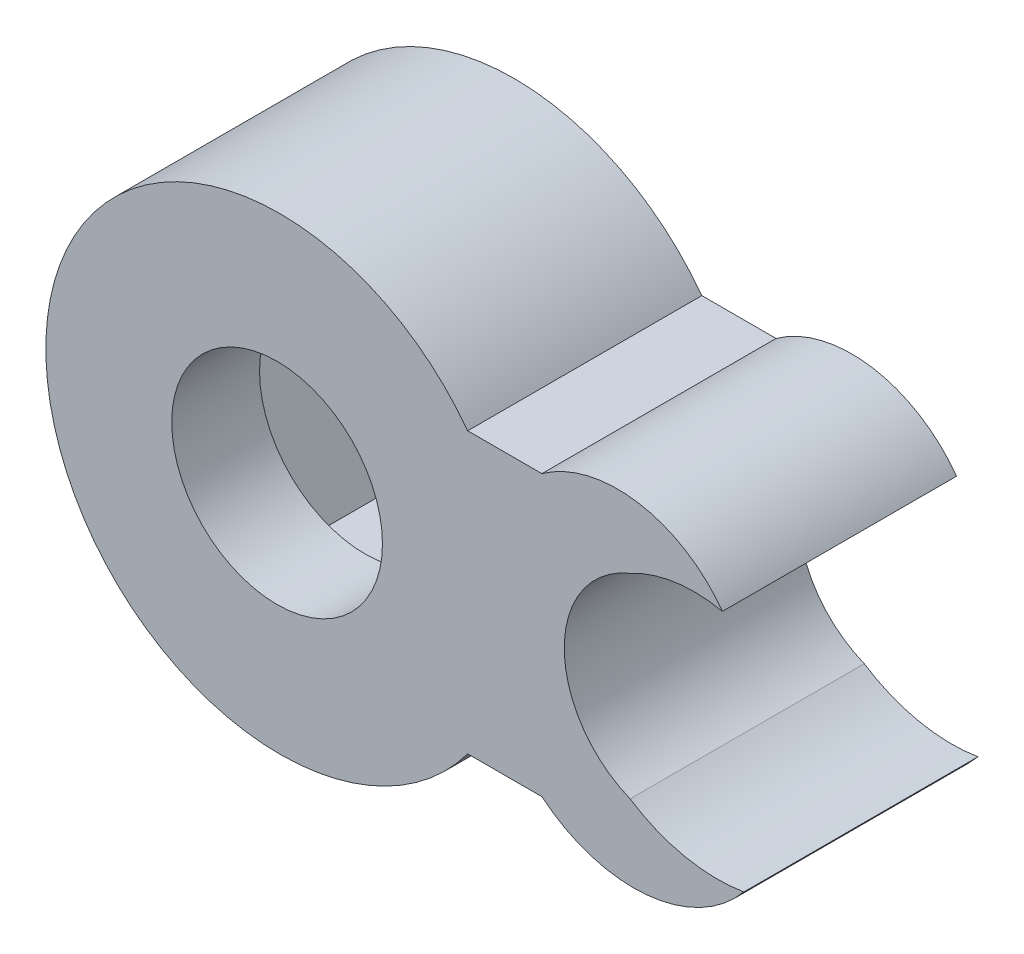
SolidWorks part; units mm, degrees
ref_plane "Plan de face" through (0, 0, 0) normal (0, 0, 1) x (1, 0, 0)
ref_plane "Plan de dessus" through (0, 0, 0) normal (0, 1, 0) x (1, 0, 0)
ref_plane "Plan de droite" through (0, 0, 0) normal (1, 0, 0) x (0, 0, -1)
sketch "Esquisse1" plane through (0, 0, 0) normal (0, 0, 1) x (1, 0, 0)
  line L1 (0, 0) -> (3.17, 0)
  line L2 (0, 0) -> (0, 11.9501)
  line L3 (0, 11.9501) -> (3.17, 11.9501)
  line L4 (3.17, 0) -> (3.17, 11.9501)
  arc A0 (0, 0) -> (0, 11.9501) centre (-8.0187, 5.975) cw
  arc A1 (3.17, 11.9501) -> (3.17, 0) centre (2.6233, 5.975) cw
  dimension "D1" = 10
  dimension "D2" = 6
  dimension "D3" = 3.17
extrude "Boss.-Extru.1" add sketch "Esquisse1" along normal blind 10 contours L1 L4 L3 L2 | A0 L2 | A1 L4
sketch "Esquisse3" plane through (0, 0, 0) normal (0, 0, 1) x (1, 0, 0)
  line L1 (-4.3261, -0.7576) -> (-0.3417, 5.8066)
  line L2 (-0.3417, 5.8066) -> (-4.0343, 12.5392)
  line L3 (-4.0343, 12.5392) -> (-11.7112, 12.7077)
  line L4 (-11.7112, 12.7077) -> (-15.6956, 6.1435)
  line L5 (-15.6956, 6.1435) -> (-12.003, -0.5891)
  line L6 (-12.003, -0.5891) -> (-4.3261, -0.7576)
  circle A0 centre (-8.0187, 5.975) radius 6.65 construction
  circle A1 centre (8.6233, 5.975) radius 4.5
  arc A2 (3.17, 0) -> (3.17, 11.9501) centre (2.6233, 5.975) ccw construction
  dimension "D1" = 13.3
  dimension "D2" = 9
extrude "Enlèv. mat.-Extru.1" cut sketch "Esquisse3" along normal blind 6.25
sketch "Esquisse4" plane through (0, 0, 6.25) normal (0, 0, -1) x (-1, 0, 0)
  circle A0 centre (8.141, 5.9514) radius 4.5
  dimension "D1" = 9
extrude "Enlèv. mat.-Extru.2" cut sketch "Esquisse4" against normal blind 10
sketch "Esquisse6" plane through (0, 0, 6.25) normal (0, 0, -1) x (-1, 0, 0)
  arc A0 (-6.9358, 1.8034) -> (-6.9358, 10.1467) centre (-2.6233, 5.975) cw
  arc A1 (-6.9358, 10.1467) -> (-6.9358, 1.8034) centre (-8.6233, 5.975) cw
extrude "Enlèv. mat.-Extru.4" cut sketch "Esquisse6" against normal blind 10
sketch "Esquisse7" plane through (0, 0, 0) normal (0, 0, -1) x (-1, 0, 0)
  arc A0 (-3.17, 0) -> (-11.7952, 0.7892) centre (-7.088, 4.7072) cw
  arc A1 (-11.7952, 0.7892) -> (-6.9358, 1.8034) centre (-10.6684, 7.5388) ccw
  arc A2 (-6.9358, 1.8034) -> (-3.17, 0) centre (-2.6233, 5.975) ccw
extrude "Boss.-Extru.3" add sketch "Esquisse7" against normal blind 10
sketch "Esquisse8" plane through (0, 0, 0) normal (0, 0, -1) x (-1, 0, 0)
  arc A0 (-3.17, 11.9501) -> (-10.8797, 10.7103) centre (-6.405, 7.4753) ccw
  arc A1 (-6.9358, 10.1467) -> (-10.8797, 10.7103) centre (-9.6777, 5.0406) ccw
  arc A2 (-6.9358, 10.1467) -> (-3.17, 11.9501) centre (-2.6233, 5.975) cw
extrude "Boss.-Extru.4" add sketch "Esquisse8" against normal blind 10
